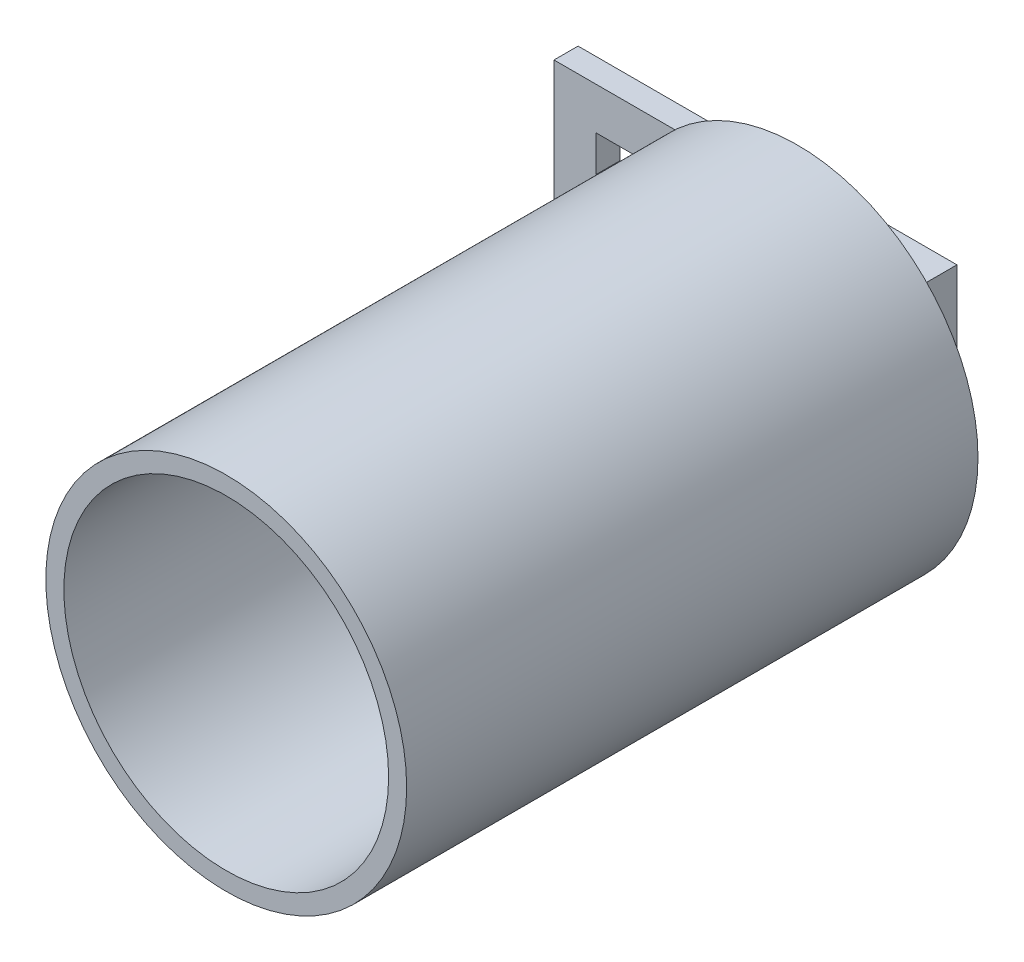
SolidWorks part; units mm, degrees
ref_plane "Plan de face" through (0, 0, 0) normal (0, 0, 1) x (1, 0, 0)
ref_plane "Plan de dessus" through (0, 0, 0) normal (0, 1, 0) x (1, 0, 0)
ref_plane "Plan de droite" through (0, 0, 0) normal (1, 0, 0) x (0, 0, -1)
sketch "Esquisse1" plane through (0, 0, 0) normal (0, 0, 1) x (1, 0, 0)
  circle A0 centre (0, 0) radius 30
  dimension "D1" = 60
extrude "Boss.-Extru.1" add sketch "Esquisse1" along normal blind 95 contours A0
sketch "Esquisse2" plane through (0, 0, 95) normal (0, 0, 1) x (1, 0, 0)
  circle A0 centre (0, 0) radius 27
  circle A1 centre (0, 0) radius 30 construction
  dimension "D1" = 3
extrude "Enlèv. mat.-Extru.1" cut sketch "Esquisse2" against normal blind 80 contours A0
sketch "Esquisse3" plane through (0, 0, 0) normal (0, 0, -1) x (-1, 0, 0)
  line L1 (-10.5, -10) -> (10.5, -10)
  line L2 (-10.5, -10) -> (-10.5, 10)
  line L3 (-10.5, 10) -> (10.5, 10)
  line L4 (10.5, -10) -> (10.5, 10)
  line L5 (-10.5, -10) -> (10.5, 10) construction
  line L6 (-10.5, 10) -> (10.5, -10) construction
  point P0 (0, 0)
  dimension "D1" = 20
  dimension "D2" = 21
extrude "Boss.-Extru.2" add sketch "Esquisse3" along normal blind 16
sketch "Esquisse4" plane through (-10.5, 0, 0) normal (-1, 0, 0) x (0, 0, 1)
  line L0 (0, -10) -> (0, 10) construction
  line L1 (-16, 10) -> (-12, 10)
  line L2 (-16, 10) -> (-16, -10)
  line L3 (-16, -10) -> (-12, -10)
  line L4 (-12, 10) -> (-12, -10)
  line L5 (-16, 10) -> (-12, -10) construction
  line L6 (-16, -10) -> (-12, 10) construction
  line L7 (-16, 10) -> (0, 10) construction
  line L8 (-16, -10) -> (0, -10) construction
  point P0 (-14, 0)
  dimension "D1" = 12
  dimension "D2" = 4
  dimension "D3" = 0
  dimension "D4" = 0
extrude "Boss.-Extru.3" add sketch "Esquisse4" along normal blind 42
sketch "Esquisse5" plane through (0, 0, -16) normal (0, 0, -1) x (-1, 0, 0)
  line L0 (-10.5, -10) -> (52.5, -10) construction
  line L1 (35.5, -3) -> (45.5, -3)
  line L2 (35.5, -3) -> (35.5, 3)
  line L3 (35.5, 3) -> (45.5, 3)
  line L4 (45.5, -3) -> (45.5, 3)
  line L5 (35.5, -3) -> (45.5, 3) construction
  line L6 (35.5, 3) -> (45.5, -3) construction
  line L8 (52.5, 10) -> (52.5, -10) construction
  point P0 (40.5, 0)
  dimension "D1" = 6
  dimension "D2" = 10
  dimension "D3" = 7
  dimension "D4" = 7
extrude "Enlèv. mat.-Extru.2" cut sketch "Esquisse5" against normal up to next
equation "\"taille\"= 3mm"
